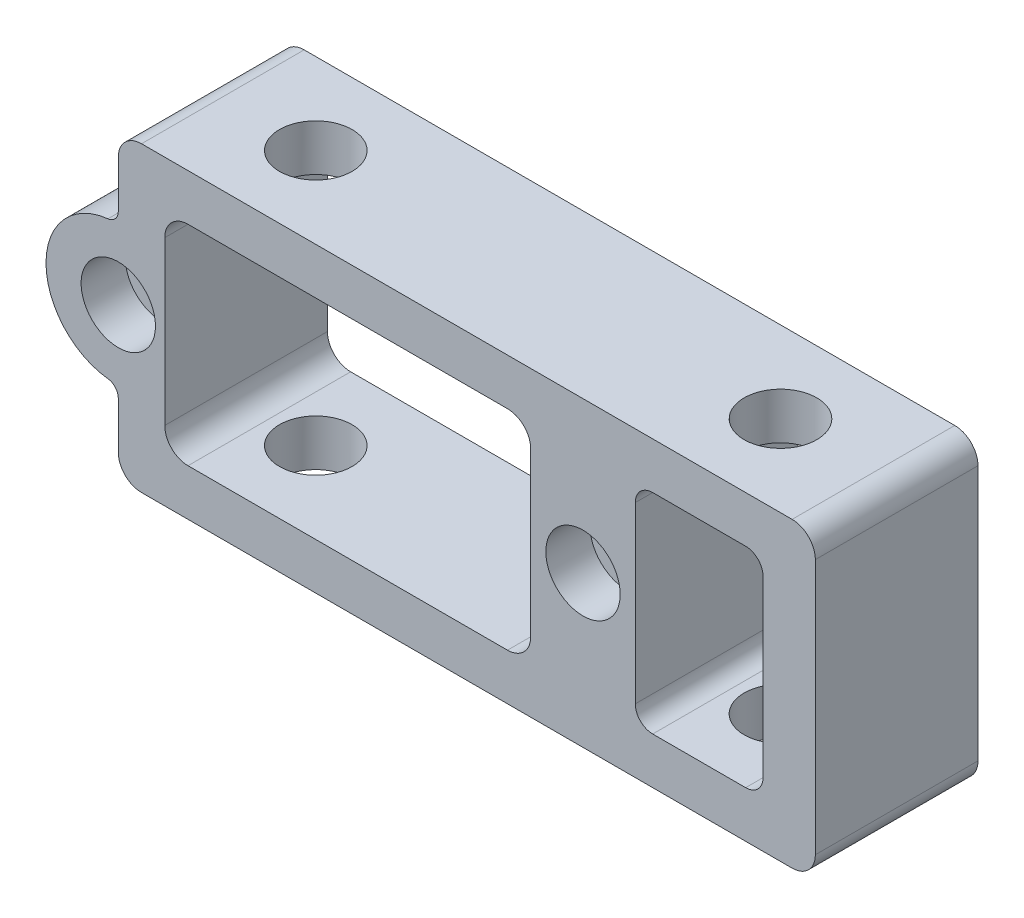
SolidWorks part; units mm, degrees
material "7075-T6, Plate (SS)"
ref_plane "X-Y Datum" through (0, 0, 0) normal (0, 0, 1) x (1, 0, 0)
ref_plane "X-Z Datum" through (0, 0, 0) normal (0, 1, 0) x (1, 0, 0)
ref_plane "Y-Z Datum" through (0, 0, 0) normal (1, 0, 0) x (0, 0, -1)
other "Center of Mass"
other "Graphic1"
other "Graphic (Closed) -1"
other "Graphic2"
other "Graphic (Closed) -2"
other "Graphic3"
other "Graphic (Closed) -3"
sketch "Sketch1" plane through (0, 0, 0) normal (0, 1, 0) x (1, 0, 0)
  line L0 (101.6, 8.89) -> (76.2, 8.89) construction
  line L1 (101.6, 17.78) -> (0, 17.78)
  line L2 (101.6, 17.78) -> (101.6, 0)
  line L3 (101.6, 0) -> (0, 0)
  line L5 (0, 31.6293) -> (0, -17.6841) construction
  line L6 (0, 17.78) -> (0, 0)
  line L7 (76.2, 8.89) -> (25.4, 8.89) construction
  line L8 (25.4, 8.89) -> (0, 8.89) construction
  circle A0 centre (76.2, 8.89) radius 3.9688
  circle A1 centre (25.4, 8.89) radius 3.9687
  point P12 (50.8, 8.89)
  point P13 (50.8, 17.78)
  dimension "D3" = 7.9375
  dimension "D1" = 101.6
  dimension "D2" = 17.78
  dimension "D4" = 50.8
extrude "Boss-Extrude1" add sketch "Sketch1" against normal blind 33.02
sketch "Sketch2" plane through (0, 0, 0) normal (0, 0, 1) x (1, 0, 0)
  line L4 (0, -33.02) -> (0, 0) construction
  line L5 (0, -33.02) -> (101.6, -33.02) construction
  line L8 (101.6, -33.02) -> (101.6, 0) construction
  circle A0 centre (63.5, -16.51) radius 2.4892
  circle A1 centre (12.7, -16.51) radius 2.4892
  dimension "D3" = 4.9784
  dimension "D1" = 12.7
  dimension "D5" = 16.51
  dimension "D6" = 38.1
  dimension "D2" = 16.51
extrude "Cut-Extrude1" cut sketch "Sketch2" against normal up to surface (17.78 mm away) up to face at (50.8, -16.51, -17.78)
sketch "Sketch3" plane through (0, 0, 0) normal (0, 0, 1) x (1, 0, 0)
  circle A0 centre (63.5, -16.51) radius 4.064
  circle A3 centre (12.7, -16.51) radius 4.064
  circle A4 centre (12.7, -16.51) radius 2.4892 construction
  dimension "D1" = 8.128
extrude "Cut-Extrude2" cut sketch "Sketch3" against normal blind 4.826
ref_plane "Plane1" through (0, -16.51, 0) normal (0, 1, 0) x (1, 0, 0)
ref_plane "Plane2" through (0, -16.51, 0) normal (0, 1, 0) x (1, 0, 0)
sketch "Sketch5" plane through (0, 0, 0) normal (0, 0, 1) x (1, 0, 0)
  line L8 (0, -33.02) -> (101.6, -33.02) construction
  line L18 (0, -33.02) -> (0, 0) construction
  line L19 (50.8, 0) -> (50.8, -33.02) construction
  line L20 (0, 0) -> (101.6, 0) construction
  line B0 (12.7, -7.675) -> (12.7, 0)
  line B1 (0, 0) -> (12.7, 0)
  line B2 (0, -33.02) -> (0, 0)
  line B3 (12.7, -33.02) -> (0, -33.02)
  line B4 (12.7, -25.345) -> (12.7, -33.02)
  arc B5 (12.7, -7.675) -> (11.5711, -8.9372) centre (11.43, -7.675) cw
  arc B6 (12.7, -25.345) -> (11.5711, -24.0828) centre (11.43, -25.345) ccw
  arc B7 (11.5711, -24.0828) -> (11.5711, -8.9372) centre (12.4178, -16.51) cw
  line B8 (88.9, -7.675) -> (88.9, 0)
  line B9 (101.6, 0) -> (88.9, 0)
  line B10 (101.6, -33.02) -> (101.6, 0)
  line B11 (88.9, -33.02) -> (101.6, -33.02)
  line B12 (88.9, -25.345) -> (88.9, -33.02)
  arc B13 (88.9, -7.675) -> (90.0289, -8.9372) centre (90.17, -7.675) ccw
  arc B14 (88.9, -25.345) -> (90.0289, -24.0828) centre (90.17, -25.345) cw
  arc B15 (90.0289, -24.0828) -> (90.0289, -8.9372) centre (89.1822, -16.51) ccw
sketch_block_instance "Block2-1"
sketch_block "Block2" parameters "D1"=10.16
sketch_block_instance "Block2-2"
extrude "Cut-Extrude3" cut sketch "Sketch5" against normal through all
fillet "Fillet1" radius 2.54 4 edges at (12.7, 0, -8.89) (88.9, 0, -8.89) (88.9, -33.02, -8.89) (12.7, -33.02, -8.89)
ref_point "Point1"
ref_point "Point2"
sketch "Sketch6" plane through (0, 0, 0) normal (0, 0, 1) x (1, 0, 0)
  line L0 (50.8, 0) -> (50.8, -33.02) construction
  line L1 (15.24, 0) -> (86.36, 0) construction
  line L2 (15.24, -33.02) -> (86.36, -33.02) construction
  line L3 (12.7, -30.48) -> (12.7, -25.345) construction
  line L5 (17.78, -25.4) -> (17.78, -7.62)
  line L7 (57.785, -25.4) -> (57.785, -7.62)
  line L8 (69.215, -5.08) -> (69.215, -27.94)
  line L9 (69.215, -27.94) -> (83.185, -27.94)
  line L10 (83.185, -27.94) -> (83.185, -5.08)
  line L11 (83.185, -5.08) -> (69.215, -5.08)
  line L12 (88.9, -7.675) -> (88.9, -25.345)
  line L13 (88.9, -25.345) -> (99.8485, -25.345)
  line L14 (99.8485, -25.345) -> (99.8485, -7.675)
  line L15 (99.8485, -7.675) -> (88.9, -7.675)
  line L18 (20.32, -27.94) -> (55.245, -27.94)
  line L21 (20.32, -5.08) -> (55.245, -5.08)
  arc A0 (20.32, -27.94) -> (17.78, -25.4) centre (20.32, -25.4) cw
  arc A1 (55.245, -27.94) -> (57.785, -25.4) centre (55.245, -25.4) ccw
  arc A2 (55.245, -5.08) -> (57.785, -7.62) centre (55.245, -7.62) cw
  arc A3 (17.78, -7.62) -> (20.32, -5.08) centre (20.32, -7.62) cw
  point P6 (50.8, -16.51)
  point P23 (17.78, -16.51)
  point P30 (69.215, -16.51)
  point P33 (57.785, -16.51)
  dimension "D3" = 2.54
  dimension "D1" = 40.005
  dimension "D4" = 5.08
  dimension "D5" = 11.43
  dimension "D6" = 22.86
  dimension "D7" = 13.97
  dimension "D8" = 16.51
extrude "Cut-Extrude4" cut sketch "Sketch6" against normal through all
fillet "Fillet2" radius 1.905 4 edges at (69.215, -27.94, -8.89) (83.185, -27.94, -8.89) (83.185, -5.08, -8.89) (69.215, -5.08, -8.89)
